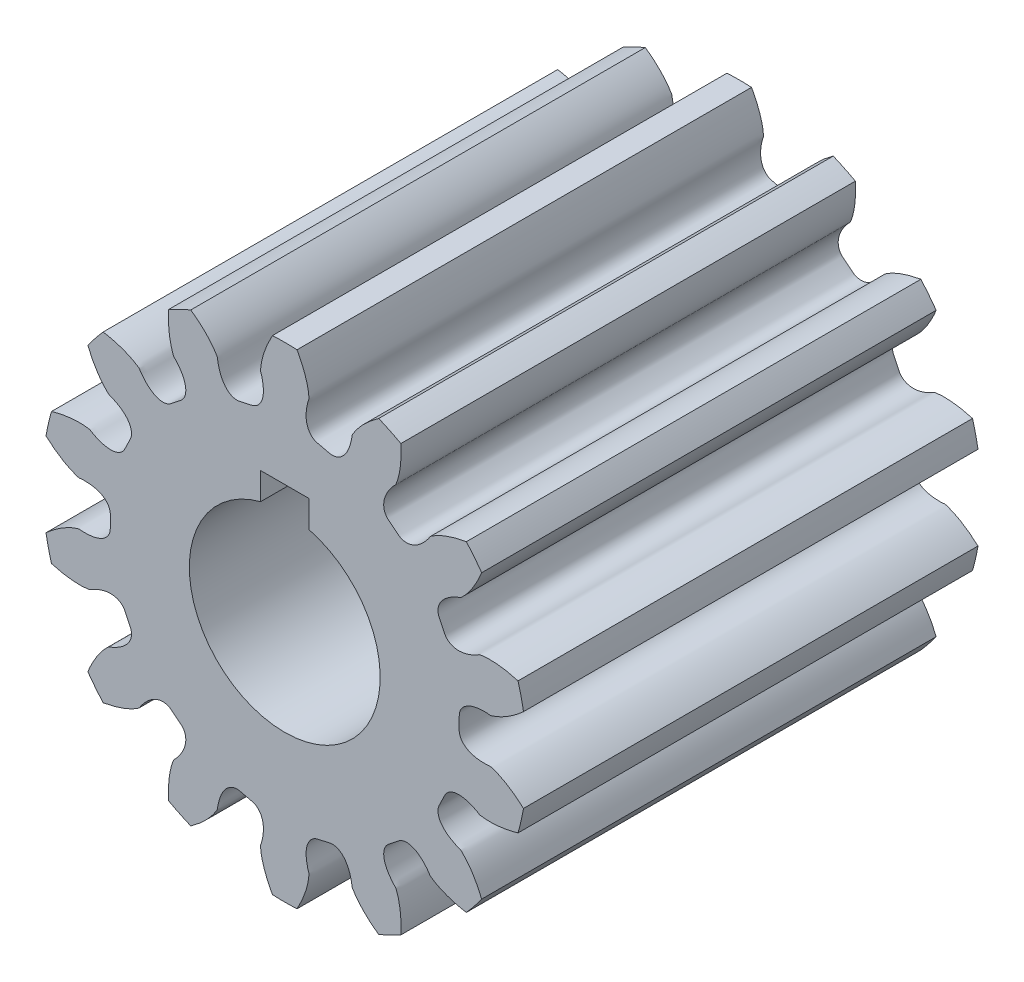
SolidWorks part; units mm, degrees
material "AISI 4130 Steel, annealed at 865C"
ref_plane "Front Plane" through (0, 0, 0) normal (0, 0, 1) x (1, 0, 0)
ref_plane "Top Plane" through (0, 0, 0) normal (0, 1, 0) x (1, 0, 0)
ref_plane "Right Plane" through (0, 0, 0) normal (1, 0, 0) x (0, 0, -1)
ref_plane "Plane1" through (0, 0, 9.525) normal (0, 0, 1) x (1, 0, 0)
sketch "Sketch1" plane through (0, 0, 9.525) normal (0, 0, 1) x (1, 0, 0)
  line L0 (1.01, 5) -> (1.01, 3.8704)
  line L1 (-1.01, 3.8704) -> (-1.01, 5)
  line L2 (-1.01, 5) -> (1.01, 5)
  arc A0 (1.01, 3.8704) -> (-1.01, 3.8704) centre (0, 0) cw
  arc A1 (8.2542, 5.9239) -> (7.6122, 6.7291) centre (0, 0) ccw
  arc A2 (4.8665, 8.9187) -> (3.9387, 9.3655) centre (0, 0) ccw
  arc A3 (0.5149, 10.1469) -> (-0.5149, 10.1469) centre (0, 0) ccw
  arc A4 (-3.9387, 9.3655) -> (-4.8665, 8.9187) centre (0, 0) ccw
  arc A5 (-7.6122, 6.7291) -> (-8.2542, 5.9239) centre (0, 0) ccw
  arc A6 (-9.778, 2.7599) -> (-10.0071, 1.7559) centre (0, 0) ccw
  arc A7 (-10.0071, -1.7559) -> (-9.778, -2.7599) centre (0, 0) ccw
  arc A8 (-8.2542, -5.9239) -> (-7.6122, -6.7291) centre (0, 0) ccw
  arc A9 (-4.8665, -8.9187) -> (-3.9387, -9.3655) centre (0, 0) ccw
  arc A10 (-0.5149, -10.1469) -> (0.5149, -10.1469) centre (0, 0) ccw
  arc A11 (3.9387, -9.3655) -> (4.8665, -8.9187) centre (0, 0) ccw
  arc A12 (7.6122, -6.7291) -> (8.2542, -5.9239) centre (0, 0) ccw
  arc A13 (9.778, -2.7599) -> (10.0071, -1.7559) centre (0, 0) ccw
  arc A14 (10.0071, 1.7559) -> (9.778, 2.7599) centre (0, 0) ccw
  spline S0 degree 3 poles (8.2542, 5.9239) (8.2213, 5.8435) (8.1658, 5.7165) (8.0838, 5.5483) (8.0156, 5.4193) (7.9477, 5.3002) (7.8807, 5.1908) (7.8151, 5.0911) (7.7514, 5.0008) (7.6901, 4.9196) (7.6319, 4.8472) (7.5771, 4.7835) (7.5263, 4.7282) (7.4801, 4.6804) (7.4277, 4.6319) (7.3617, 4.5626) (7.2605, 4.5412) (7.1763, 4.501) (7.1095, 4.4698) (7.046, 4.4368) (6.9852, 4.4028) (6.9274, 4.3677) (6.8725, 4.3315) (6.8204, 4.2943) (6.7711, 4.2559) (6.7247, 4.2165) (6.681, 4.1758) (6.64, 4.1337) (6.6019, 4.0902) (6.5666, 4.045) (6.5342, 3.9978) (6.5048, 3.9483) (6.4789, 3.8961) (6.4567, 3.8408) (6.4391, 3.782) (6.4268, 3.7194) (6.4213, 3.6531) (6.4238, 3.5836) (6.4357, 3.5122) (6.4562, 3.4476) (6.5069, 3.3338) (6.5953, 3.1761) (6.6635, 3.0087) (6.7208, 2.8982) (6.7585, 2.8418) (6.807, 2.788) (6.8597, 2.7427) (6.915, 2.7057) (6.9716, 2.6762) (7.0286, 2.6533) (7.0856, 2.6362) (7.1426, 2.6239) (7.1996, 2.616) (7.2567, 2.6119) (7.3141, 2.6114) (7.3719, 2.6141) (7.4303, 2.6199) (7.4893, 2.6286) (7.5492, 2.6404) (7.6099, 2.655) (7.6715, 2.6725) (7.734, 2.6929) (7.7975, 2.7162) (7.8619, 2.7424) (7.9273, 2.7715) (7.9934, 2.8043) (8.0773, 2.8451) (8.1571, 2.9109) (8.2524, 2.9193) (8.3231, 2.93) (8.3892, 2.9363) (8.4642, 2.9416) (8.5481, 2.9446) (8.641, 2.9451) (8.7427, 2.9423) (8.853, 2.9358) (8.9719, 2.9249) (9.0992, 2.9092) (9.2346, 2.888) (9.378, 2.8608) (9.5607, 2.8201) (9.6945, 2.7844) (9.778, 2.7599) knots 0.010403 0.010403 0.010403 0.010403 0.046486 0.067894 0.088079 0.107041 0.124779 0.141294 0.156585 0.170653 0.183498 0.19512 0.205518 0.214693 0.222644 0.235305 0.253444 0.263936 0.274129 0.28403 0.293651 0.303001 0.312093 0.320945 0.329573 0.337998 0.346246 0.354347 0.362336 0.370253 0.378149 0.386081 0.394114 0.402321 0.410779 0.419564 0.428738 0.438336 0.448346 0.458697 0.466397 0.5 0.533603 0.541303 0.551654 0.561664 0.571262 0.580436 0.589221 0.597679 0.605886 0.613919 0.621851 0.629747 0.637664 0.645653 0.653754 0.662002 0.670427 0.679055 0.687907 0.696999 0.706349 0.71597 0.725871 0.736064 0.746556 0.764695 0.777356 0.785307 0.794482 0.80488 0.816502 0.829347 0.843415 0.858706 0.875221 0.892959 0.911921 0.932106 0.953514 0.989597 0.989597 0.989597 0.989597
  spline S1 degree 3 poles (4.8665, 8.9187) (4.8718, 8.8319) (4.8769, 8.6934) (4.8759, 8.5062) (4.8705, 8.3604) (4.861, 8.2237) (4.848, 8.0961) (4.8322, 7.9778) (4.814, 7.8687) (4.7941, 7.769) (4.773, 7.6786) (4.7513, 7.5974) (4.7295, 7.5255) (4.7086, 7.4624) (4.6824, 7.3959) (4.653, 7.3049) (4.5711, 7.2417) (4.5127, 7.169) (4.466, 7.1119) (4.4231, 7.0545) (4.3832, 6.9976) (4.3463, 6.9409) (4.3125, 6.8844) (4.2818, 6.8283) (4.254, 6.7724) (4.2293, 6.7166) (4.2076, 6.661) (4.1889, 6.6054) (4.1734, 6.5496) (4.1612, 6.4936) (4.1525, 6.437) (4.1475, 6.3797) (4.1468, 6.3214) (4.1508, 6.2619) (4.1604, 6.2013) (4.1766, 6.1396) (4.2003, 6.0774) (4.2327, 6.0159) (4.2744, 5.9567) (4.321, 5.9074) (4.416, 5.8269) (4.5641, 5.7232) (4.6981, 5.6019) (4.7978, 5.5272) (4.8562, 5.4928) (4.9232, 5.4653) (4.9904, 5.4474) (5.0563, 5.4381) (5.12, 5.436) (5.1813, 5.4402) (5.2401, 5.4494) (5.2968, 5.4631) (5.3516, 5.4807) (5.4048, 5.5018) (5.4567, 5.5262) (5.5076, 5.5537) (5.5577, 5.5843) (5.6071, 5.6178) (5.656, 5.6543) (5.7043, 5.6938) (5.7522, 5.7363) (5.7997, 5.7818) (5.8468, 5.8304) (5.8934, 5.882) (5.9398, 5.9366) (5.985, 5.9948) (6.043, 6.0679) (6.0863, 6.1618) (6.1686, 6.2108) (6.2276, 6.2511) (6.2844, 6.2855) (6.3496, 6.3227) (6.424, 6.3619) (6.5074, 6.4026) (6.6002, 6.4442) (6.7025, 6.4862) (6.8143, 6.528) (6.9358, 6.5691) (7.067, 6.6087) (7.208, 6.6465) (7.3902, 6.6891) (7.5264, 6.7149) (7.6122, 6.7291) knots 0.010403 0.010403 0.010403 0.010403 0.046486 0.067894 0.088079 0.107041 0.124779 0.141294 0.156585 0.170653 0.183498 0.19512 0.205518 0.214693 0.222644 0.235305 0.253444 0.263936 0.274129 0.28403 0.293651 0.303001 0.312093 0.320945 0.329573 0.337998 0.346246 0.354347 0.362336 0.370253 0.378149 0.386081 0.394114 0.402321 0.410779 0.419564 0.428738 0.438336 0.448346 0.458697 0.466397 0.5 0.533603 0.541303 0.551654 0.561664 0.571262 0.580436 0.589221 0.597679 0.605886 0.613919 0.621851 0.629747 0.637664 0.645653 0.653754 0.662002 0.670427 0.679055 0.687907 0.696999 0.706349 0.71597 0.725871 0.736064 0.746556 0.764695 0.777356 0.785307 0.794482 0.80488 0.816502 0.829347 0.843415 0.858706 0.875221 0.892959 0.911921 0.932106 0.953514 0.989597 0.989597 0.989597 0.989597
  spline S2 degree 3 poles (0.5149, 10.1469) (0.5573, 10.071) (0.622, 9.9485) (0.7023, 9.7794) (0.7607, 9.6457) (0.8115, 9.5184) (0.8552, 9.3978) (0.8922, 9.2843) (0.9231, 9.1782) (0.9485, 9.0797) (0.9687, 8.9891) (0.9844, 8.9065) (0.9959, 8.8323) (1.0044, 8.7664) (1.0098, 8.6951) (1.0228, 8.6003) (0.9764, 8.5079) (0.9553, 8.417) (0.938, 8.3453) (0.9243, 8.275) (0.913, 8.2064) (0.9044, 8.1393) (0.8984, 8.0738) (0.8951, 8.0099) (0.8943, 7.9474) (0.8962, 7.8865) (0.9008, 7.8269) (0.9081, 7.7687) (0.9183, 7.7118) (0.9317, 7.656) (0.9483, 7.6012) (0.9688, 7.5474) (0.9934, 7.4946) (1.0228, 7.4428) (1.0578, 7.3923) (1.0991, 7.3437) (1.1475, 7.298) (1.2034, 7.2567) (1.2666, 7.2215) (1.33, 7.1972) (1.4505, 7.1659) (1.6289, 7.1367) (1.8023, 7.0856) (1.9245, 7.0615) (1.9921, 7.0559) (2.0644, 7.0602) (2.1327, 7.0732) (2.1961, 7.0934) (2.2544, 7.1192) (2.3078, 7.1495) (2.3568, 7.1834) (2.4019, 7.2203) (2.4436, 7.2599) (2.4824, 7.302) (2.5186, 7.3465) (2.5526, 7.3934) (2.5844, 7.4427) (2.6144, 7.4943) (2.6425, 7.5484) (2.6689, 7.605) (2.6937, 7.6641) (2.7167, 7.7257) (2.7381, 7.7898) (2.7577, 7.8566) (2.7758, 7.9259) (2.7913, 7.998) (2.8117, 8.089) (2.8101, 8.1924) (2.8629, 8.2722) (2.8986, 8.3341) (2.9349, 8.3897) (2.9775, 8.4516) (3.0275, 8.5192) (3.085, 8.592) (3.1505, 8.6698) (3.2245, 8.752) (3.3071, 8.8382) (3.3987, 8.9279) (3.4997, 9.0205) (3.6104, 9.1157) (3.7561, 9.2331) (3.8675, 9.3155) (3.9387, 9.3655) knots 0.010403 0.010403 0.010403 0.010403 0.046486 0.067894 0.088079 0.107041 0.124779 0.141294 0.156585 0.170653 0.183498 0.19512 0.205518 0.214693 0.222644 0.235305 0.253444 0.263936 0.274129 0.28403 0.293651 0.303001 0.312093 0.320945 0.329573 0.337998 0.346246 0.354347 0.362336 0.370253 0.378149 0.386081 0.394114 0.402321 0.410779 0.419564 0.428738 0.438336 0.448346 0.458697 0.466397 0.5 0.533603 0.541303 0.551654 0.561664 0.571262 0.580436 0.589221 0.597679 0.605886 0.613919 0.621851 0.629747 0.637664 0.645653 0.653754 0.662002 0.670427 0.679055 0.687907 0.696999 0.706349 0.71597 0.725871 0.736064 0.746556 0.764695 0.777356 0.785307 0.794482 0.80488 0.816502 0.829347 0.843415 0.858706 0.875221 0.892959 0.911921 0.932106 0.953514 0.989597 0.989597 0.989597 0.989597
  spline S3 degree 3 poles (-3.9387, 9.3655) (-3.8675, 9.3155) (-3.7561, 9.2331) (-3.6104, 9.1157) (-3.4997, 9.0205) (-3.3987, 8.9279) (-3.3071, 8.8382) (-3.2245, 8.752) (-3.1505, 8.6698) (-3.085, 8.592) (-3.0275, 8.5192) (-2.9775, 8.4516) (-2.9349, 8.3897) (-2.8986, 8.3341) (-2.8629, 8.2722) (-2.8101, 8.1924) (-2.8117, 8.089) (-2.7913, 7.998) (-2.7758, 7.9259) (-2.7577, 7.8566) (-2.7381, 7.7898) (-2.7167, 7.7257) (-2.6937, 7.6641) (-2.6689, 7.605) (-2.6425, 7.5484) (-2.6144, 7.4943) (-2.5844, 7.4427) (-2.5526, 7.3934) (-2.5186, 7.3465) (-2.4824, 7.302) (-2.4436, 7.2599) (-2.4019, 7.2203) (-2.3568, 7.1834) (-2.3078, 7.1495) (-2.2544, 7.1192) (-2.1961, 7.0934) (-2.1327, 7.0732) (-2.0644, 7.0602) (-1.9921, 7.0559) (-1.9245, 7.0615) (-1.8023, 7.0856) (-1.6289, 7.1367) (-1.4505, 7.1659) (-1.33, 7.1972) (-1.2666, 7.2215) (-1.2034, 7.2567) (-1.1475, 7.298) (-1.0991, 7.3437) (-1.0578, 7.3923) (-1.0228, 7.4428) (-0.9934, 7.4946) (-0.9688, 7.5474) (-0.9483, 7.6012) (-0.9317, 7.656) (-0.9183, 7.7118) (-0.9081, 7.7687) (-0.9008, 7.8269) (-0.8962, 7.8865) (-0.8943, 7.9474) (-0.8951, 8.0099) (-0.8984, 8.0738) (-0.9044, 8.1393) (-0.913, 8.2064) (-0.9243, 8.275) (-0.938, 8.3453) (-0.9553, 8.417) (-0.9764, 8.5079) (-1.0228, 8.6003) (-1.0098, 8.6951) (-1.0044, 8.7664) (-0.9959, 8.8323) (-0.9844, 8.9065) (-0.9687, 8.9891) (-0.9485, 9.0797) (-0.9231, 9.1782) (-0.8922, 9.2843) (-0.8552, 9.3978) (-0.8115, 9.5184) (-0.7607, 9.6457) (-0.7023, 9.7794) (-0.622, 9.9485) (-0.5573, 10.071) (-0.5149, 10.1469) knots 0.010403 0.010403 0.010403 0.010403 0.046486 0.067894 0.088079 0.107041 0.124779 0.141294 0.156585 0.170653 0.183498 0.19512 0.205518 0.214693 0.222644 0.235305 0.253444 0.263936 0.274129 0.28403 0.293651 0.303001 0.312093 0.320945 0.329573 0.337998 0.346246 0.354347 0.362336 0.370253 0.378149 0.386081 0.394114 0.402321 0.410779 0.419564 0.428738 0.438336 0.448346 0.458697 0.466397 0.5 0.533603 0.541303 0.551654 0.561664 0.571262 0.580436 0.589221 0.597679 0.605886 0.613919 0.621851 0.629747 0.637664 0.645653 0.653754 0.662002 0.670427 0.679055 0.687907 0.696999 0.706349 0.71597 0.725871 0.736064 0.746556 0.764695 0.777356 0.785307 0.794482 0.80488 0.816502 0.829347 0.843415 0.858706 0.875221 0.892959 0.911921 0.932106 0.953514 0.989597 0.989597 0.989597 0.989597
  spline S4 degree 3 poles (-7.6122, 6.7291) (-7.5264, 6.7149) (-7.3902, 6.6891) (-7.208, 6.6465) (-7.067, 6.6087) (-6.9358, 6.5691) (-6.8143, 6.528) (-6.7025, 6.4862) (-6.6002, 6.4442) (-6.5074, 6.4026) (-6.424, 6.3619) (-6.3496, 6.3227) (-6.2844, 6.2855) (-6.2276, 6.2511) (-6.1686, 6.2108) (-6.0863, 6.1618) (-6.043, 6.0679) (-5.985, 5.9948) (-5.9398, 5.9366) (-5.8934, 5.882) (-5.8468, 5.8304) (-5.7997, 5.7818) (-5.7522, 5.7363) (-5.7043, 5.6938) (-5.656, 5.6543) (-5.6071, 5.6178) (-5.5577, 5.5843) (-5.5076, 5.5537) (-5.4567, 5.5262) (-5.4048, 5.5018) (-5.3516, 5.4807) (-5.2968, 5.4631) (-5.2401, 5.4494) (-5.1813, 5.4402) (-5.12, 5.436) (-5.0563, 5.4381) (-4.9904, 5.4474) (-4.9232, 5.4653) (-4.8562, 5.4928) (-4.7978, 5.5272) (-4.6981, 5.6019) (-4.5641, 5.7232) (-4.416, 5.8269) (-4.321, 5.9074) (-4.2744, 5.9567) (-4.2327, 6.0159) (-4.2003, 6.0774) (-4.1766, 6.1396) (-4.1604, 6.2013) (-4.1508, 6.2619) (-4.1468, 6.3214) (-4.1475, 6.3797) (-4.1525, 6.437) (-4.1612, 6.4936) (-4.1734, 6.5496) (-4.1889, 6.6054) (-4.2076, 6.661) (-4.2293, 6.7166) (-4.254, 6.7724) (-4.2818, 6.8283) (-4.3125, 6.8844) (-4.3463, 6.9409) (-4.3832, 6.9976) (-4.4231, 7.0545) (-4.466, 7.1119) (-4.5127, 7.169) (-4.5711, 7.2417) (-4.653, 7.3049) (-4.6824, 7.3959) (-4.7086, 7.4624) (-4.7295, 7.5255) (-4.7513, 7.5974) (-4.773, 7.6786) (-4.7941, 7.769) (-4.814, 7.8687) (-4.8322, 7.9778) (-4.848, 8.0961) (-4.861, 8.2237) (-4.8705, 8.3604) (-4.8759, 8.5062) (-4.8769, 8.6934) (-4.8718, 8.8319) (-4.8665, 8.9187) knots 0.010403 0.010403 0.010403 0.010403 0.046486 0.067894 0.088079 0.107041 0.124779 0.141294 0.156585 0.170653 0.183498 0.19512 0.205518 0.214693 0.222644 0.235305 0.253444 0.263936 0.274129 0.28403 0.293651 0.303001 0.312093 0.320945 0.329573 0.337998 0.346246 0.354347 0.362336 0.370253 0.378149 0.386081 0.394114 0.402321 0.410779 0.419564 0.428738 0.438336 0.448346 0.458697 0.466397 0.5 0.533603 0.541303 0.551654 0.561664 0.571262 0.580436 0.589221 0.597679 0.605886 0.613919 0.621851 0.629747 0.637664 0.645653 0.653754 0.662002 0.670427 0.679055 0.687907 0.696999 0.706349 0.71597 0.725871 0.736064 0.746556 0.764695 0.777356 0.785307 0.794482 0.80488 0.816502 0.829347 0.843415 0.858706 0.875221 0.892959 0.911921 0.932106 0.953514 0.989597 0.989597 0.989597 0.989597
  spline S5 degree 3 poles (-9.778, 2.7599) (-9.6945, 2.7844) (-9.5607, 2.8201) (-9.378, 2.8608) (-9.2346, 2.888) (-9.0992, 2.9092) (-8.9719, 2.9249) (-8.853, 2.9358) (-8.7427, 2.9423) (-8.641, 2.9451) (-8.5481, 2.9446) (-8.4642, 2.9416) (-8.3892, 2.9363) (-8.3231, 2.93) (-8.2524, 2.9193) (-8.1571, 2.9109) (-8.0773, 2.8451) (-7.9934, 2.8043) (-7.9273, 2.7715) (-7.8619, 2.7424) (-7.7975, 2.7162) (-7.734, 2.6929) (-7.6715, 2.6725) (-7.6099, 2.655) (-7.5492, 2.6404) (-7.4893, 2.6286) (-7.4303, 2.6199) (-7.3719, 2.6141) (-7.3141, 2.6114) (-7.2567, 2.6119) (-7.1996, 2.616) (-7.1426, 2.6239) (-7.0856, 2.6362) (-7.0286, 2.6533) (-6.9716, 2.6762) (-6.915, 2.7057) (-6.8597, 2.7427) (-6.807, 2.788) (-6.7585, 2.8418) (-6.7208, 2.8982) (-6.6635, 3.0087) (-6.5953, 3.1761) (-6.5069, 3.3338) (-6.4562, 3.4476) (-6.4357, 3.5122) (-6.4238, 3.5836) (-6.4213, 3.6531) (-6.4268, 3.7194) (-6.4391, 3.782) (-6.4567, 3.8408) (-6.4789, 3.8961) (-6.5048, 3.9483) (-6.5342, 3.9978) (-6.5666, 4.045) (-6.6019, 4.0902) (-6.64, 4.1337) (-6.681, 4.1758) (-6.7247, 4.2165) (-6.7711, 4.2559) (-6.8204, 4.2943) (-6.8725, 4.3315) (-6.9274, 4.3677) (-6.9852, 4.4028) (-7.046, 4.4368) (-7.1095, 4.4698) (-7.1763, 4.501) (-7.2605, 4.5412) (-7.3617, 4.5626) (-7.4277, 4.6319) (-7.4801, 4.6804) (-7.5263, 4.7282) (-7.5771, 4.7835) (-7.6319, 4.8472) (-7.6901, 4.9196) (-7.7514, 5.0008) (-7.8151, 5.0911) (-7.8807, 5.1908) (-7.9477, 5.3002) (-8.0156, 5.4193) (-8.0838, 5.5483) (-8.1658, 5.7165) (-8.2213, 5.8435) (-8.2542, 5.9239) knots 0.010403 0.010403 0.010403 0.010403 0.046486 0.067894 0.088079 0.107041 0.124779 0.141294 0.156585 0.170653 0.183498 0.19512 0.205518 0.214693 0.222644 0.235305 0.253444 0.263936 0.274129 0.28403 0.293651 0.303001 0.312093 0.320945 0.329573 0.337998 0.346246 0.354347 0.362336 0.370253 0.378149 0.386081 0.394114 0.402321 0.410779 0.419564 0.428738 0.438336 0.448346 0.458697 0.466397 0.5 0.533603 0.541303 0.551654 0.561664 0.571262 0.580436 0.589221 0.597679 0.605886 0.613919 0.621851 0.629747 0.637664 0.645653 0.653754 0.662002 0.670427 0.679055 0.687907 0.696999 0.706349 0.71597 0.725871 0.736064 0.746556 0.764695 0.777356 0.785307 0.794482 0.80488 0.816502 0.829347 0.843415 0.858706 0.875221 0.892959 0.911921 0.932106 0.953514 0.989597 0.989597 0.989597 0.989597
  spline S6 degree 3 poles (-10.0071, -1.7559) (-9.9426, -1.6977) (-9.8375, -1.6074) (-9.6905, -1.4914) (-9.5731, -1.4047) (-9.4603, -1.3269) (-9.3525, -1.2575) (-9.2501, -1.1961) (-9.1535, -1.1423) (-9.0631, -1.0957) (-8.9792, -1.0559) (-8.9023, -1.0222) (-8.8324, -0.9944) (-8.7701, -0.9714) (-8.7018, -0.9504) (-8.6123, -0.9166) (-8.5118, -0.9413) (-8.4186, -0.9416) (-8.3448, -0.9425) (-8.2732, -0.9403) (-8.2038, -0.936) (-8.1365, -0.9295) (-8.0713, -0.9207) (-8.0082, -0.9097) (-7.9472, -0.8966) (-7.8882, -0.8812) (-7.8311, -0.8635) (-7.776, -0.8434) (-7.7228, -0.8207) (-7.6713, -0.7953) (-7.6217, -0.7669) (-7.5738, -0.735) (-7.5277, -0.6992) (-7.4838, -0.659) (-7.4423, -0.6137) (-7.4042, -0.5626) (-7.3704, -0.5053) (-7.3425, -0.4416) (-7.3222, -0.3721) (-7.3127, -0.3049) (-7.309, -0.1804) (-7.3203, 0) (-7.309, 0.1804) (-7.3127, 0.3049) (-7.3222, 0.3721) (-7.3425, 0.4416) (-7.3704, 0.5053) (-7.4042, 0.5626) (-7.4423, 0.6137) (-7.4838, 0.659) (-7.5277, 0.6992) (-7.5738, 0.735) (-7.6217, 0.7669) (-7.6713, 0.7953) (-7.7228, 0.8207) (-7.776, 0.8434) (-7.8311, 0.8635) (-7.8882, 0.8812) (-7.9472, 0.8966) (-8.0082, 0.9097) (-8.0713, 0.9207) (-8.1365, 0.9295) (-8.2038, 0.936) (-8.2732, 0.9403) (-8.3448, 0.9425) (-8.4186, 0.9416) (-8.5118, 0.9413) (-8.6123, 0.9166) (-8.7018, 0.9504) (-8.7701, 0.9714) (-8.8324, 0.9944) (-8.9023, 1.0222) (-8.9792, 1.0559) (-9.0631, 1.0957) (-9.1535, 1.1423) (-9.2501, 1.1961) (-9.3525, 1.2575) (-9.4603, 1.3269) (-9.5731, 1.4047) (-9.6905, 1.4914) (-9.8375, 1.6074) (-9.9426, 1.6977) (-10.0071, 1.7559) knots 0.010403 0.010403 0.010403 0.010403 0.046486 0.067894 0.088079 0.107041 0.124779 0.141294 0.156585 0.170653 0.183498 0.19512 0.205518 0.214693 0.222644 0.235305 0.253444 0.263936 0.274129 0.28403 0.293651 0.303001 0.312093 0.320945 0.329573 0.337998 0.346246 0.354347 0.362336 0.370253 0.378149 0.386081 0.394114 0.402321 0.410779 0.419564 0.428738 0.438336 0.448346 0.458697 0.466397 0.5 0.533603 0.541303 0.551654 0.561664 0.571262 0.580436 0.589221 0.597679 0.605886 0.613919 0.621851 0.629747 0.637664 0.645653 0.653754 0.662002 0.670427 0.679055 0.687907 0.696999 0.706349 0.71597 0.725871 0.736064 0.746556 0.764695 0.777356 0.785307 0.794482 0.80488 0.816502 0.829347 0.843415 0.858706 0.875221 0.892959 0.911921 0.932106 0.953514 0.989597 0.989597 0.989597 0.989597
  spline S7 degree 3 poles (-8.2542, -5.9239) (-8.2213, -5.8435) (-8.1658, -5.7165) (-8.0838, -5.5483) (-8.0156, -5.4193) (-7.9477, -5.3002) (-7.8807, -5.1908) (-7.8151, -5.0911) (-7.7514, -5.0008) (-7.6901, -4.9196) (-7.6319, -4.8472) (-7.5771, -4.7835) (-7.5263, -4.7282) (-7.4801, -4.6804) (-7.4277, -4.6319) (-7.3617, -4.5626) (-7.2605, -4.5412) (-7.1763, -4.501) (-7.1095, -4.4698) (-7.046, -4.4368) (-6.9852, -4.4028) (-6.9274, -4.3677) (-6.8725, -4.3315) (-6.8204, -4.2943) (-6.7711, -4.2559) (-6.7247, -4.2165) (-6.681, -4.1758) (-6.64, -4.1337) (-6.6019, -4.0902) (-6.5666, -4.045) (-6.5342, -3.9978) (-6.5048, -3.9483) (-6.4789, -3.8961) (-6.4567, -3.8408) (-6.4391, -3.782) (-6.4268, -3.7194) (-6.4213, -3.6531) (-6.4238, -3.5836) (-6.4357, -3.5122) (-6.4562, -3.4476) (-6.5069, -3.3338) (-6.5953, -3.1761) (-6.6635, -3.0087) (-6.7208, -2.8982) (-6.7585, -2.8418) (-6.807, -2.788) (-6.8597, -2.7427) (-6.915, -2.7057) (-6.9716, -2.6762) (-7.0286, -2.6533) (-7.0856, -2.6362) (-7.1426, -2.6239) (-7.1996, -2.616) (-7.2567, -2.6119) (-7.3141, -2.6114) (-7.3719, -2.6141) (-7.4303, -2.6199) (-7.4893, -2.6286) (-7.5492, -2.6404) (-7.6099, -2.655) (-7.6715, -2.6725) (-7.734, -2.6929) (-7.7975, -2.7162) (-7.8619, -2.7424) (-7.9273, -2.7715) (-7.9934, -2.8043) (-8.0773, -2.8451) (-8.1571, -2.9109) (-8.2524, -2.9193) (-8.3231, -2.93) (-8.3892, -2.9363) (-8.4642, -2.9416) (-8.5481, -2.9446) (-8.641, -2.9451) (-8.7427, -2.9423) (-8.853, -2.9358) (-8.9719, -2.9249) (-9.0992, -2.9092) (-9.2346, -2.888) (-9.378, -2.8608) (-9.5607, -2.8201) (-9.6945, -2.7844) (-9.778, -2.7599) knots 0.010403 0.010403 0.010403 0.010403 0.046486 0.067894 0.088079 0.107041 0.124779 0.141294 0.156585 0.170653 0.183498 0.19512 0.205518 0.214693 0.222644 0.235305 0.253444 0.263936 0.274129 0.28403 0.293651 0.303001 0.312093 0.320945 0.329573 0.337998 0.346246 0.354347 0.362336 0.370253 0.378149 0.386081 0.394114 0.402321 0.410779 0.419564 0.428738 0.438336 0.448346 0.458697 0.466397 0.5 0.533603 0.541303 0.551654 0.561664 0.571262 0.580436 0.589221 0.597679 0.605886 0.613919 0.621851 0.629747 0.637664 0.645653 0.653754 0.662002 0.670427 0.679055 0.687907 0.696999 0.706349 0.71597 0.725871 0.736064 0.746556 0.764695 0.777356 0.785307 0.794482 0.80488 0.816502 0.829347 0.843415 0.858706 0.875221 0.892959 0.911921 0.932106 0.953514 0.989597 0.989597 0.989597 0.989597
  spline S8 degree 3 poles (-4.8665, -8.9187) (-4.8718, -8.8319) (-4.8769, -8.6934) (-4.8759, -8.5062) (-4.8705, -8.3604) (-4.861, -8.2237) (-4.848, -8.0961) (-4.8322, -7.9778) (-4.814, -7.8687) (-4.7941, -7.769) (-4.773, -7.6786) (-4.7513, -7.5974) (-4.7295, -7.5255) (-4.7086, -7.4624) (-4.6824, -7.3959) (-4.653, -7.3049) (-4.5711, -7.2417) (-4.5127, -7.169) (-4.466, -7.1119) (-4.4231, -7.0545) (-4.3832, -6.9976) (-4.3463, -6.9409) (-4.3125, -6.8844) (-4.2818, -6.8283) (-4.254, -6.7724) (-4.2293, -6.7166) (-4.2076, -6.661) (-4.1889, -6.6054) (-4.1734, -6.5496) (-4.1612, -6.4936) (-4.1525, -6.437) (-4.1475, -6.3797) (-4.1468, -6.3214) (-4.1508, -6.2619) (-4.1604, -6.2013) (-4.1766, -6.1396) (-4.2003, -6.0774) (-4.2327, -6.0159) (-4.2744, -5.9567) (-4.321, -5.9074) (-4.416, -5.8269) (-4.5641, -5.7232) (-4.6981, -5.6019) (-4.7978, -5.5272) (-4.8562, -5.4928) (-4.9232, -5.4653) (-4.9904, -5.4474) (-5.0563, -5.4381) (-5.12, -5.436) (-5.1813, -5.4402) (-5.2401, -5.4494) (-5.2968, -5.4631) (-5.3516, -5.4807) (-5.4048, -5.5018) (-5.4567, -5.5262) (-5.5076, -5.5537) (-5.5577, -5.5843) (-5.6071, -5.6178) (-5.656, -5.6543) (-5.7043, -5.6938) (-5.7522, -5.7363) (-5.7997, -5.7818) (-5.8468, -5.8304) (-5.8934, -5.882) (-5.9398, -5.9366) (-5.985, -5.9948) (-6.043, -6.0679) (-6.0863, -6.1618) (-6.1686, -6.2108) (-6.2276, -6.2511) (-6.2844, -6.2855) (-6.3496, -6.3227) (-6.424, -6.3619) (-6.5074, -6.4026) (-6.6002, -6.4442) (-6.7025, -6.4862) (-6.8143, -6.528) (-6.9358, -6.5691) (-7.067, -6.6087) (-7.208, -6.6465) (-7.3902, -6.6891) (-7.5264, -6.7149) (-7.6122, -6.7291) knots 0.010403 0.010403 0.010403 0.010403 0.046486 0.067894 0.088079 0.107041 0.124779 0.141294 0.156585 0.170653 0.183498 0.19512 0.205518 0.214693 0.222644 0.235305 0.253444 0.263936 0.274129 0.28403 0.293651 0.303001 0.312093 0.320945 0.329573 0.337998 0.346246 0.354347 0.362336 0.370253 0.378149 0.386081 0.394114 0.402321 0.410779 0.419564 0.428738 0.438336 0.448346 0.458697 0.466397 0.5 0.533603 0.541303 0.551654 0.561664 0.571262 0.580436 0.589221 0.597679 0.605886 0.613919 0.621851 0.629747 0.637664 0.645653 0.653754 0.662002 0.670427 0.679055 0.687907 0.696999 0.706349 0.71597 0.725871 0.736064 0.746556 0.764695 0.777356 0.785307 0.794482 0.80488 0.816502 0.829347 0.843415 0.858706 0.875221 0.892959 0.911921 0.932106 0.953514 0.989597 0.989597 0.989597 0.989597
  spline S9 degree 3 poles (-0.5149, -10.1469) (-0.5573, -10.071) (-0.622, -9.9485) (-0.7023, -9.7794) (-0.7607, -9.6457) (-0.8115, -9.5184) (-0.8552, -9.3978) (-0.8922, -9.2843) (-0.9231, -9.1782) (-0.9485, -9.0797) (-0.9687, -8.9891) (-0.9844, -8.9065) (-0.9959, -8.8323) (-1.0044, -8.7664) (-1.0098, -8.6951) (-1.0228, -8.6003) (-0.9764, -8.5079) (-0.9553, -8.417) (-0.938, -8.3453) (-0.9243, -8.275) (-0.913, -8.2064) (-0.9044, -8.1393) (-0.8984, -8.0738) (-0.8951, -8.0099) (-0.8943, -7.9474) (-0.8962, -7.8865) (-0.9008, -7.8269) (-0.9081, -7.7687) (-0.9183, -7.7118) (-0.9317, -7.656) (-0.9483, -7.6012) (-0.9688, -7.5474) (-0.9934, -7.4946) (-1.0228, -7.4428) (-1.0578, -7.3923) (-1.0991, -7.3437) (-1.1475, -7.298) (-1.2034, -7.2567) (-1.2666, -7.2215) (-1.33, -7.1972) (-1.4505, -7.1659) (-1.6289, -7.1367) (-1.8023, -7.0856) (-1.9245, -7.0615) (-1.9921, -7.0559) (-2.0644, -7.0602) (-2.1327, -7.0732) (-2.1961, -7.0934) (-2.2544, -7.1192) (-2.3078, -7.1495) (-2.3568, -7.1834) (-2.4019, -7.2203) (-2.4436, -7.2599) (-2.4824, -7.302) (-2.5186, -7.3465) (-2.5526, -7.3934) (-2.5844, -7.4427) (-2.6144, -7.4943) (-2.6425, -7.5484) (-2.6689, -7.605) (-2.6937, -7.6641) (-2.7167, -7.7257) (-2.7381, -7.7898) (-2.7577, -7.8566) (-2.7758, -7.9259) (-2.7913, -7.998) (-2.8117, -8.089) (-2.8101, -8.1924) (-2.8629, -8.2722) (-2.8986, -8.3341) (-2.9349, -8.3897) (-2.9775, -8.4516) (-3.0275, -8.5192) (-3.085, -8.592) (-3.1505, -8.6698) (-3.2245, -8.752) (-3.3071, -8.8382) (-3.3987, -8.9279) (-3.4997, -9.0205) (-3.6104, -9.1157) (-3.7561, -9.2331) (-3.8675, -9.3155) (-3.9387, -9.3655) knots 0.010403 0.010403 0.010403 0.010403 0.046486 0.067894 0.088079 0.107041 0.124779 0.141294 0.156585 0.170653 0.183498 0.19512 0.205518 0.214693 0.222644 0.235305 0.253444 0.263936 0.274129 0.28403 0.293651 0.303001 0.312093 0.320945 0.329573 0.337998 0.346246 0.354347 0.362336 0.370253 0.378149 0.386081 0.394114 0.402321 0.410779 0.419564 0.428738 0.438336 0.448346 0.458697 0.466397 0.5 0.533603 0.541303 0.551654 0.561664 0.571262 0.580436 0.589221 0.597679 0.605886 0.613919 0.621851 0.629747 0.637664 0.645653 0.653754 0.662002 0.670427 0.679055 0.687907 0.696999 0.706349 0.71597 0.725871 0.736064 0.746556 0.764695 0.777356 0.785307 0.794482 0.80488 0.816502 0.829347 0.843415 0.858706 0.875221 0.892959 0.911921 0.932106 0.953514 0.989597 0.989597 0.989597 0.989597
  spline S10 degree 3 poles (3.9387, -9.3655) (3.8675, -9.3155) (3.7561, -9.2331) (3.6104, -9.1157) (3.4997, -9.0205) (3.3987, -8.9279) (3.3071, -8.8382) (3.2245, -8.752) (3.1505, -8.6698) (3.085, -8.592) (3.0275, -8.5192) (2.9775, -8.4516) (2.9349, -8.3897) (2.8986, -8.3341) (2.8629, -8.2722) (2.8101, -8.1924) (2.8117, -8.089) (2.7913, -7.998) (2.7758, -7.9259) (2.7577, -7.8566) (2.7381, -7.7898) (2.7167, -7.7257) (2.6937, -7.6641) (2.6689, -7.605) (2.6425, -7.5484) (2.6144, -7.4943) (2.5844, -7.4427) (2.5526, -7.3934) (2.5186, -7.3465) (2.4824, -7.302) (2.4436, -7.2599) (2.4019, -7.2203) (2.3568, -7.1834) (2.3078, -7.1495) (2.2544, -7.1192) (2.1961, -7.0934) (2.1327, -7.0732) (2.0644, -7.0602) (1.9921, -7.0559) (1.9245, -7.0615) (1.8023, -7.0856) (1.6289, -7.1367) (1.4505, -7.1659) (1.33, -7.1972) (1.2666, -7.2215) (1.2034, -7.2567) (1.1475, -7.298) (1.0991, -7.3437) (1.0578, -7.3923) (1.0228, -7.4428) (0.9934, -7.4946) (0.9688, -7.5474) (0.9483, -7.6012) (0.9317, -7.656) (0.9183, -7.7118) (0.9081, -7.7687) (0.9008, -7.8269) (0.8962, -7.8865) (0.8943, -7.9474) (0.8951, -8.0099) (0.8984, -8.0738) (0.9044, -8.1393) (0.913, -8.2064) (0.9243, -8.275) (0.938, -8.3453) (0.9553, -8.417) (0.9764, -8.5079) (1.0228, -8.6003) (1.0098, -8.6951) (1.0044, -8.7664) (0.9959, -8.8323) (0.9844, -8.9065) (0.9687, -8.9891) (0.9485, -9.0797) (0.9231, -9.1782) (0.8922, -9.2843) (0.8552, -9.3978) (0.8115, -9.5184) (0.7607, -9.6457) (0.7023, -9.7794) (0.622, -9.9485) (0.5573, -10.071) (0.5149, -10.1469) knots 0.010403 0.010403 0.010403 0.010403 0.046486 0.067894 0.088079 0.107041 0.124779 0.141294 0.156585 0.170653 0.183498 0.19512 0.205518 0.214693 0.222644 0.235305 0.253444 0.263936 0.274129 0.28403 0.293651 0.303001 0.312093 0.320945 0.329573 0.337998 0.346246 0.354347 0.362336 0.370253 0.378149 0.386081 0.394114 0.402321 0.410779 0.419564 0.428738 0.438336 0.448346 0.458697 0.466397 0.5 0.533603 0.541303 0.551654 0.561664 0.571262 0.580436 0.589221 0.597679 0.605886 0.613919 0.621851 0.629747 0.637664 0.645653 0.653754 0.662002 0.670427 0.679055 0.687907 0.696999 0.706349 0.71597 0.725871 0.736064 0.746556 0.764695 0.777356 0.785307 0.794482 0.80488 0.816502 0.829347 0.843415 0.858706 0.875221 0.892959 0.911921 0.932106 0.953514 0.989597 0.989597 0.989597 0.989597
  spline S11 degree 3 poles (7.6122, -6.7291) (7.5264, -6.7149) (7.3902, -6.6891) (7.208, -6.6465) (7.067, -6.6087) (6.9358, -6.5691) (6.8143, -6.528) (6.7025, -6.4862) (6.6002, -6.4442) (6.5074, -6.4026) (6.424, -6.3619) (6.3496, -6.3227) (6.2844, -6.2855) (6.2276, -6.2511) (6.1686, -6.2108) (6.0863, -6.1618) (6.043, -6.0679) (5.985, -5.9948) (5.9398, -5.9366) (5.8934, -5.882) (5.8468, -5.8304) (5.7997, -5.7818) (5.7522, -5.7363) (5.7043, -5.6938) (5.656, -5.6543) (5.6071, -5.6178) (5.5577, -5.5843) (5.5076, -5.5537) (5.4567, -5.5262) (5.4048, -5.5018) (5.3516, -5.4807) (5.2968, -5.4631) (5.2401, -5.4494) (5.1813, -5.4402) (5.12, -5.436) (5.0563, -5.4381) (4.9904, -5.4474) (4.9232, -5.4653) (4.8562, -5.4928) (4.7978, -5.5272) (4.6981, -5.6019) (4.5641, -5.7232) (4.416, -5.8269) (4.321, -5.9074) (4.2744, -5.9567) (4.2327, -6.0159) (4.2003, -6.0774) (4.1766, -6.1396) (4.1604, -6.2013) (4.1508, -6.2619) (4.1468, -6.3214) (4.1475, -6.3797) (4.1525, -6.437) (4.1612, -6.4936) (4.1734, -6.5496) (4.1889, -6.6054) (4.2076, -6.661) (4.2293, -6.7166) (4.254, -6.7724) (4.2818, -6.8283) (4.3125, -6.8844) (4.3463, -6.9409) (4.3832, -6.9976) (4.4231, -7.0545) (4.466, -7.1119) (4.5127, -7.169) (4.5711, -7.2417) (4.653, -7.3049) (4.6824, -7.3959) (4.7086, -7.4624) (4.7295, -7.5255) (4.7513, -7.5974) (4.773, -7.6786) (4.7941, -7.769) (4.814, -7.8687) (4.8322, -7.9778) (4.848, -8.0961) (4.861, -8.2237) (4.8705, -8.3604) (4.8759, -8.5062) (4.8769, -8.6934) (4.8718, -8.8319) (4.8665, -8.9187) knots 0.010403 0.010403 0.010403 0.010403 0.046486 0.067894 0.088079 0.107041 0.124779 0.141294 0.156585 0.170653 0.183498 0.19512 0.205518 0.214693 0.222644 0.235305 0.253444 0.263936 0.274129 0.28403 0.293651 0.303001 0.312093 0.320945 0.329573 0.337998 0.346246 0.354347 0.362336 0.370253 0.378149 0.386081 0.394114 0.402321 0.410779 0.419564 0.428738 0.438336 0.448346 0.458697 0.466397 0.5 0.533603 0.541303 0.551654 0.561664 0.571262 0.580436 0.589221 0.597679 0.605886 0.613919 0.621851 0.629747 0.637664 0.645653 0.653754 0.662002 0.670427 0.679055 0.687907 0.696999 0.706349 0.71597 0.725871 0.736064 0.746556 0.764695 0.777356 0.785307 0.794482 0.80488 0.816502 0.829347 0.843415 0.858706 0.875221 0.892959 0.911921 0.932106 0.953514 0.989597 0.989597 0.989597 0.989597
  spline S12 degree 3 poles (9.778, -2.7599) (9.6945, -2.7844) (9.5607, -2.8201) (9.378, -2.8608) (9.2346, -2.888) (9.0992, -2.9092) (8.9719, -2.9249) (8.853, -2.9358) (8.7427, -2.9423) (8.641, -2.9451) (8.5481, -2.9446) (8.4642, -2.9416) (8.3892, -2.9363) (8.3231, -2.93) (8.2524, -2.9193) (8.1571, -2.9109) (8.0773, -2.8451) (7.9934, -2.8043) (7.9273, -2.7715) (7.8619, -2.7424) (7.7975, -2.7162) (7.734, -2.6929) (7.6715, -2.6725) (7.6099, -2.655) (7.5492, -2.6404) (7.4893, -2.6286) (7.4303, -2.6199) (7.3719, -2.6141) (7.3141, -2.6114) (7.2567, -2.6119) (7.1996, -2.616) (7.1426, -2.6239) (7.0856, -2.6362) (7.0286, -2.6533) (6.9716, -2.6762) (6.915, -2.7057) (6.8597, -2.7427) (6.807, -2.788) (6.7585, -2.8418) (6.7208, -2.8982) (6.6635, -3.0087) (6.5953, -3.1761) (6.5069, -3.3338) (6.4562, -3.4476) (6.4357, -3.5122) (6.4238, -3.5836) (6.4213, -3.6531) (6.4268, -3.7194) (6.4391, -3.782) (6.4567, -3.8408) (6.4789, -3.8961) (6.5048, -3.9483) (6.5342, -3.9978) (6.5666, -4.045) (6.6019, -4.0902) (6.64, -4.1337) (6.681, -4.1758) (6.7247, -4.2165) (6.7711, -4.2559) (6.8204, -4.2943) (6.8725, -4.3315) (6.9274, -4.3677) (6.9852, -4.4028) (7.046, -4.4368) (7.1095, -4.4698) (7.1763, -4.501) (7.2605, -4.5412) (7.3617, -4.5626) (7.4277, -4.6319) (7.4801, -4.6804) (7.5263, -4.7282) (7.5771, -4.7835) (7.6319, -4.8472) (7.6901, -4.9196) (7.7514, -5.0008) (7.8151, -5.0911) (7.8807, -5.1908) (7.9477, -5.3002) (8.0156, -5.4193) (8.0838, -5.5483) (8.1658, -5.7165) (8.2213, -5.8435) (8.2542, -5.9239) knots 0.010403 0.010403 0.010403 0.010403 0.046486 0.067894 0.088079 0.107041 0.124779 0.141294 0.156585 0.170653 0.183498 0.19512 0.205518 0.214693 0.222644 0.235305 0.253444 0.263936 0.274129 0.28403 0.293651 0.303001 0.312093 0.320945 0.329573 0.337998 0.346246 0.354347 0.362336 0.370253 0.378149 0.386081 0.394114 0.402321 0.410779 0.419564 0.428738 0.438336 0.448346 0.458697 0.466397 0.5 0.533603 0.541303 0.551654 0.561664 0.571262 0.580436 0.589221 0.597679 0.605886 0.613919 0.621851 0.629747 0.637664 0.645653 0.653754 0.662002 0.670427 0.679055 0.687907 0.696999 0.706349 0.71597 0.725871 0.736064 0.746556 0.764695 0.777356 0.785307 0.794482 0.80488 0.816502 0.829347 0.843415 0.858706 0.875221 0.892959 0.911921 0.932106 0.953514 0.989597 0.989597 0.989597 0.989597
  spline S13 degree 3 poles (10.0071, 1.7559) (9.9426, 1.6977) (9.8375, 1.6074) (9.6905, 1.4914) (9.5731, 1.4047) (9.4603, 1.3269) (9.3525, 1.2575) (9.2501, 1.1961) (9.1535, 1.1423) (9.0631, 1.0957) (8.9792, 1.0559) (8.9023, 1.0222) (8.8324, 0.9944) (8.7701, 0.9714) (8.7018, 0.9504) (8.6123, 0.9166) (8.5118, 0.9413) (8.4186, 0.9416) (8.3448, 0.9425) (8.2732, 0.9403) (8.2038, 0.936) (8.1365, 0.9295) (8.0713, 0.9207) (8.0082, 0.9097) (7.9472, 0.8966) (7.8882, 0.8812) (7.8311, 0.8635) (7.776, 0.8434) (7.7228, 0.8207) (7.6713, 0.7953) (7.6217, 0.7669) (7.5738, 0.735) (7.5277, 0.6992) (7.4838, 0.659) (7.4423, 0.6137) (7.4042, 0.5626) (7.3704, 0.5053) (7.3425, 0.4416) (7.3222, 0.3721) (7.3127, 0.3049) (7.309, 0.1804) (7.3203, 0) (7.309, -0.1804) (7.3127, -0.3049) (7.3222, -0.3721) (7.3425, -0.4416) (7.3704, -0.5053) (7.4042, -0.5626) (7.4423, -0.6137) (7.4838, -0.659) (7.5277, -0.6992) (7.5738, -0.735) (7.6217, -0.7669) (7.6713, -0.7953) (7.7228, -0.8207) (7.776, -0.8434) (7.8311, -0.8635) (7.8882, -0.8812) (7.9472, -0.8966) (8.0082, -0.9097) (8.0713, -0.9207) (8.1365, -0.9295) (8.2038, -0.936) (8.2732, -0.9403) (8.3448, -0.9425) (8.4186, -0.9416) (8.5118, -0.9413) (8.6123, -0.9166) (8.7018, -0.9504) (8.7701, -0.9714) (8.8324, -0.9944) (8.9023, -1.0222) (8.9792, -1.0559) (9.0631, -1.0957) (9.1535, -1.1423) (9.2501, -1.1961) (9.3525, -1.2575) (9.4603, -1.3269) (9.5731, -1.4047) (9.6905, -1.4914) (9.8375, -1.6074) (9.9426, -1.6977) (10.0071, -1.7559) knots 0.010403 0.010403 0.010403 0.010403 0.046486 0.067894 0.088079 0.107041 0.124779 0.141294 0.156585 0.170653 0.183498 0.19512 0.205518 0.214693 0.222644 0.235305 0.253444 0.263936 0.274129 0.28403 0.293651 0.303001 0.312093 0.320945 0.329573 0.337998 0.346246 0.354347 0.362336 0.370253 0.378149 0.386081 0.394114 0.402321 0.410779 0.419564 0.428738 0.438336 0.448346 0.458697 0.466397 0.5 0.533603 0.541303 0.551654 0.561664 0.571262 0.580436 0.589221 0.597679 0.605886 0.613919 0.621851 0.629747 0.637664 0.645653 0.653754 0.662002 0.670427 0.679055 0.687907 0.696999 0.706349 0.71597 0.725871 0.736064 0.746556 0.764695 0.777356 0.785307 0.794482 0.80488 0.816502 0.829347 0.843415 0.858706 0.875221 0.892959 0.911921 0.932106 0.953514 0.989597 0.989597 0.989597 0.989597
extrude "Boss-Extrude1" add sketch "Sketch1" against normal blind 19.05
sketch "Sketch2" plane through (0, 0, 9.525) normal (0, 0, 1) x (1, 0, 0)
  circle A0 centre (0, 0) radius 8.89
  dimension "D1" = 17.78
